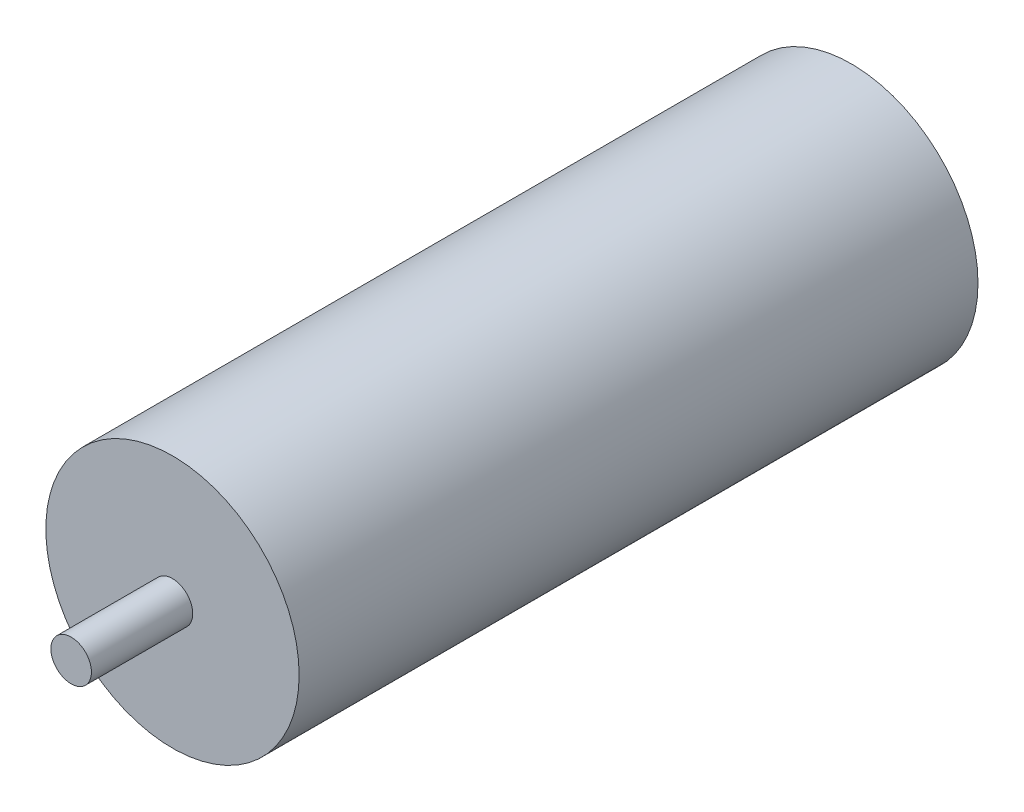
SolidWorks part; units mm, degrees
ref_plane "Plan de face" through (0, 0, 0) normal (0, 0, 1) x (1, 0, 0)
ref_plane "Plan de dessus" through (0, 0, 0) normal (0, 1, 0) x (1, 0, 0)
ref_plane "Plan de droite" through (0, 0, 0) normal (1, 0, 0) x (0, 0, -1)
sketch "Esquisse1" plane through (0, 0, 0) normal (0, 0, 1) x (1, 0, 0)
  circle A0 centre (0, 0) radius 12.5
  dimension "D1" = 25
extrude "Boss.-Extru.1" add sketch "Esquisse1" along normal blind 77
sketch "Esquisse2" plane through (0, 0, 77) normal (0, 0, 1) x (1, 0, 0)
  circle A0 centre (0, 0) radius 15.6929
  circle A1 centre (0, 0) radius 2
  dimension "D1" = 4
extrude "Enlèv. mat.-Extru.1" cut sketch "Esquisse2" against normal blind 10
